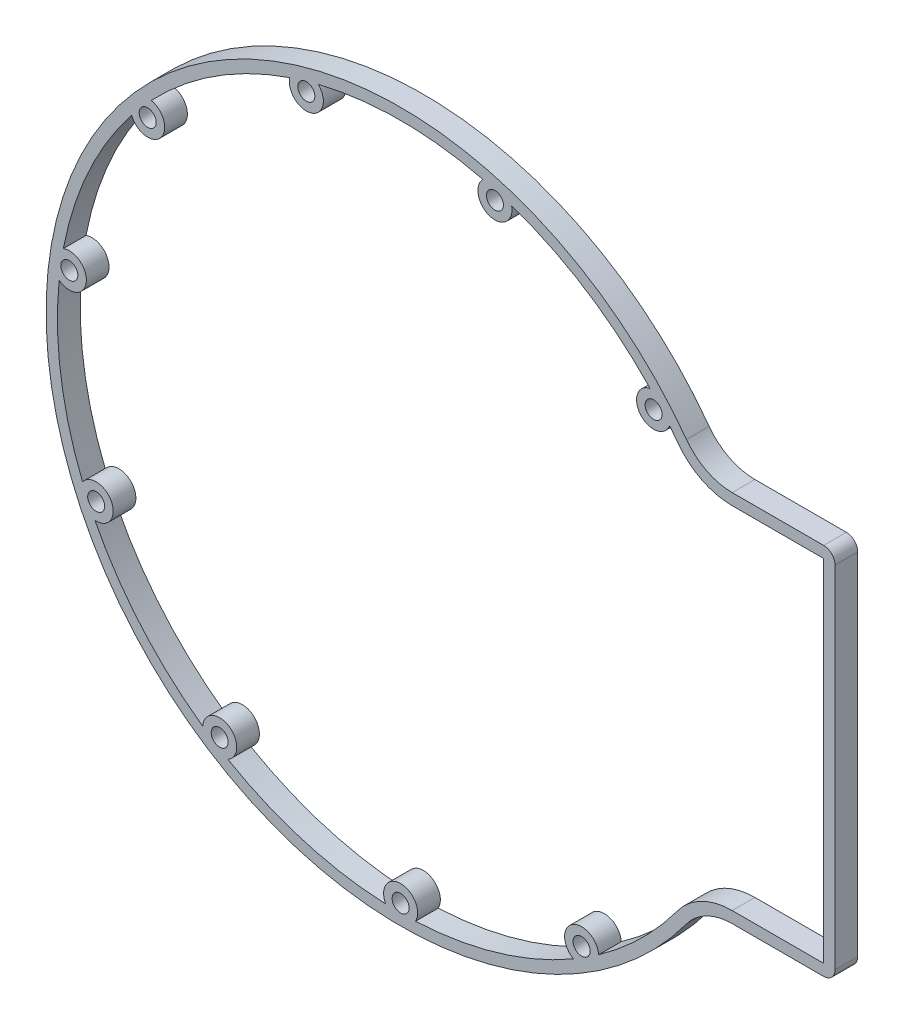
SolidWorks part; units mm, degrees
ref_plane "前视基准面" through (0, 0, 0) normal (0, 0, 1) x (1, 0, 0)
ref_plane "上视基准面" through (0, 0, 0) normal (0, 1, 0) x (1, 0, 0)
ref_plane "右视基准面" through (0, 0, 0) normal (1, 0, 0) x (0, 0, -1)
sketch "草图1" plane through (0, 0, 0) normal (0, 0, 1) x (1, 0, 0)
  line L2 (0, 0) -> (-102.4397, 0) construction
  line L3 (0, 1.2542) -> (0, 77.8801) construction
  line L4 (0, 0) -> (118.6635, 0) construction
  line L5 (0, 0) -> (0, -124.4057) construction
  line L25 (0, 0) -> (30.8589, 32.9) construction
  line L45 (58.4452, 32.9) -> (74.5685, 32.9)
  line L46 (58.4452, -32.9) -> (74.5685, -32.9)
  line L47 (76.5685, -30.9) -> (76.5685, 30.9)
  line L56 (58.4452, -30.9) -> (74.5685, -30.9)
  line L57 (74.5685, -30.9) -> (74.5685, 30.9)
  line L58 (58.4452, 30.9) -> (74.5685, 30.9)
  circle A0 centre (0, 0) radius 59 construction
  circle A2 centre (0, 0) radius 62.5 construction
  circle A4 centre (0, -59) radius 1.5
  circle A8 centre (-31.8978, -49.634) radius 1.5
  circle A9 centre (-53.6683, -24.5095) radius 1.5
  circle A10 centre (-58.3995, 8.3966) radius 1.5
  circle A11 centre (-44.5892, 38.6368) radius 1.5
  circle A12 centre (-16.6222, 56.6101) radius 1.5
  circle A13 centre (16.6222, 56.6101) radius 1.5
  circle A14 centre (44.5892, 38.6368) radius 1.5
  circle A17 centre (31.8978, -49.634) radius 1.5
  circle A65 centre (64.5685, 25.9) radius 1.5 construction
  arc A76 (50.3838, 36.9828) -> (50.3838, -36.9828) centre (0, 0) ccw
  arc A77 (58.4452, 32.9) -> (50.3838, 36.9828) centre (58.4452, 42.9) cw
  arc A78 (58.4452, -32.9) -> (50.3838, -36.9828) centre (58.4452, -42.9) ccw
  arc A85 (74.5685, -32.9) -> (76.5685, -30.9) centre (74.5685, -30.9) ccw
  arc A86 (74.5685, 32.9) -> (76.5685, 30.9) centre (74.5685, 30.9) cw
  arc A87 (48.7715, 35.7993) -> (48.7715, -35.7993) centre (0, 0) ccw construction
  arc A88 (58.4452, -30.9) -> (48.7715, -35.7993) centre (58.4452, -42.9) ccw
  arc A89 (74.5685, -30.9) -> (74.5685, -30.9) centre (74.5685, -30.9) ccw
  arc A90 (74.5685, 30.9) -> (74.5685, 30.9) centre (74.5685, 30.9) cw
  arc A91 (58.4452, 30.9) -> (48.7715, 35.7993) centre (58.4452, 42.9) cw
  circle A92 centre (44.5892, 38.6368) radius 3 construction
  arc A93 (47.4021, 37.5938) -> (43.9572, 41.5694) centre (44.5892, 38.6368) cw
  arc A94 (43.9572, 41.5694) -> (19.5524, 57.2534) centre (0, 0) ccw
  arc A96 (30.4651, -52.2697) -> (34.8906, -49.4257) centre (31.8978, -49.634) cw
  arc A97 (-2.6303, -60.4428) -> (2.6303, -60.4428) centre (0, -59) cw
  arc A98 (-34.8906, -49.4257) -> (-30.4651, -52.2697) centre (-31.8978, -49.634) cw
  arc A99 (-56.0734, -22.7163) -> (-53.888, -27.5014) centre (-53.6683, -24.5095) cw
  arc A100 (-59.4532, 11.2054) -> (-60.2019, 5.9984) centre (-58.3995, 8.3966) cw
  arc A101 (-43.9572, 41.5694) -> (-47.4021, 37.5938) centre (-44.5892, 38.6368) cw
  arc A102 (-14.505, 58.7355) -> (-19.5524, 57.2534) centre (-16.6222, 56.6101) cw
  arc A103 (19.5524, 57.2534) -> (14.505, 58.7355) centre (16.6222, 56.6101) cw
  arc A104 (60.2019, 5.9984) -> (59.4532, 11.2054) centre (58.3995, 8.3966) cw [skipped]
  arc A105 (14.505, 58.7355) -> (-14.505, 58.7355) centre (0, 0) ccw
  arc A106 (-19.5524, 57.2534) -> (-43.9572, 41.5694) centre (0, 0) ccw
  arc A107 (-59.4532, 11.2054) -> (-47.4021, 37.5938) centre (0, 0) cw
  arc A108 (-60.2019, 5.9984) -> (-56.0734, -22.7163) centre (0, 0) ccw
  arc A109 (-53.888, -27.5014) -> (-34.8906, -49.4257) centre (0, 0) ccw
  arc A110 (-30.4651, -52.2697) -> (-2.6303, -60.4428) centre (0, 0) ccw
  arc A111 (2.6303, -60.4428) -> (30.4651, -52.2697) centre (0, 0) ccw
  arc A112 (34.8906, -49.4257) -> (48.7715, -35.7993) centre (0, 0) ccw
  arc A113 (47.4021, 37.5938) -> (48.7715, 35.7993) centre (0, 0) cw
  arc A118 (53.888, -27.5014) -> (56.0734, -22.7163) centre (53.6683, -24.5095) cw [skipped]
  circle A119 centre (58.3995, 8.3966) radius 1.5 construction
  circle A120 centre (53.6683, -24.5095) radius 1.5 construction
  point P164 (53.1398, 32.9)
  point P166 (53.1398, -32.9)
  dimension "D1" = 125
  dimension "D2" = 118
  dimension "D5" = 3
  dimension "D34" = 10
  dimension "D38" = 11
  dimension "D37" = 2
  dimension "D7" = 11
extrude "凸台-拉伸1" add sketch "草图1" along normal blind 4 contours A2
